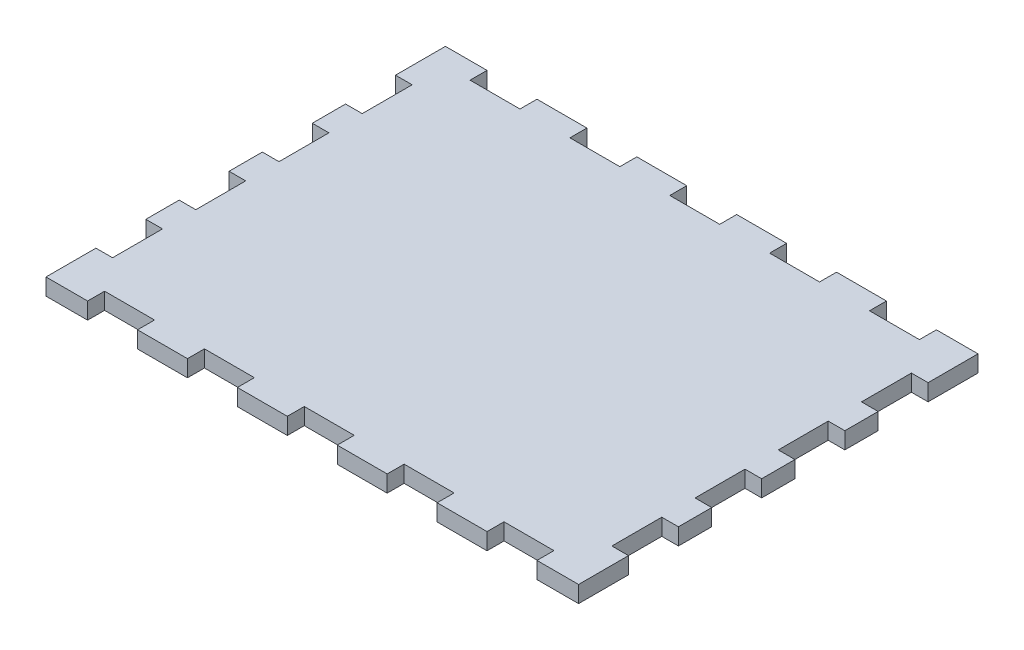
SolidWorks part; units mm, degrees
material "PINE"
ref_plane "Front Plane" through (0, 0, 0) normal (0, 0, 1) x (1, 0, 0)
ref_plane "Top Plane" through (0, 0, 0) normal (0, 1, 0) x (1, 0, 0)
ref_plane "Right Plane" through (0, 0, 0) normal (1, 0, 0) x (0, 0, -1)
sketch "Sketch1" plane through (0, 0, 0) normal (0, 1, 0) x (1, 0, 0)
  line L0 (101.6, 76.2) -> (-101.6, 76.2)
  line L2 (-101.6, 76.2) -> (-101.6, -76.2)
  line L3 (-101.6, -76.2) -> (101.6, -76.2)
  line L4 (101.6, 76.2) -> (101.6, -76.2)
  line L5 (-101.6, 76.2) -> (101.6, -76.2) construction
  line L6 (-101.6, -76.2) -> (101.6, 76.2) construction
  point P0 (0, 0)
  dimension "D2" = 152.4
  dimension "D7" = 203.2
extrude "Boss-Extrude1" add sketch "Sketch1" along normal mid plane 6.35
sketch "Sketch2" plane through (0, 3.175, 0) normal (0, 1, 0) x (1, 0, 0)
  line L0 (101.6, 76.2) -> (-101.6, 76.2) construction
  line L1 (85.725, 76.2) -> (66.675, 76.2)
  line L2 (85.725, 76.2) -> (85.725, 69.723)
  line L3 (85.725, 69.723) -> (66.675, 69.723)
  line L4 (66.675, 76.2) -> (66.675, 69.723)
  line L5 (101.6, -76.2) -> (101.6, 76.2) construction
  dimension "D1" = 19.05
  dimension "D2" = 15.875
  dimension "D3" = 6.477
extrude "Cut-Extrude1" cut sketch "Sketch2" against normal through all
pattern_linear "LPattern1" count 5 spacing 38.1 along (-1, 0, 0) of "Cut-Extrude1"
mirror "Mirror1" about plane through (0, 0, 0) normal (0, 0, 1) of "LPattern1", "Cut-Extrude1"
sketch "Sketch3" plane through (0, 3.175, 0) normal (0, 1, 0) x (1, 0, 0)
  line L0 (-101.6, 76.2) -> (-101.6, -76.2) construction
  line L1 (-101.6, 57.15) -> (-95.25, 57.15)
  line L2 (-101.6, 57.15) -> (-101.6, 38.1)
  line L3 (-101.6, 38.1) -> (-95.25, 38.1)
  line L4 (-95.25, 57.15) -> (-95.25, 38.1)
  line L5 (-85.725, 76.2) -> (-101.6, 76.2) construction
  dimension "D1" = 19.05
  dimension "D2" = 6.35
  dimension "D3" = 19.05
extrude "Cut-Extrude2" cut sketch "Sketch3" against normal through all
pattern_linear "LPattern2" count 4 spacing 31.75 along (0, 0, 1) of "Cut-Extrude2"
mirror "Mirror2" about plane through (0, 0, 0) normal (1, 0, 0) of "LPattern2", "Cut-Extrude2"
